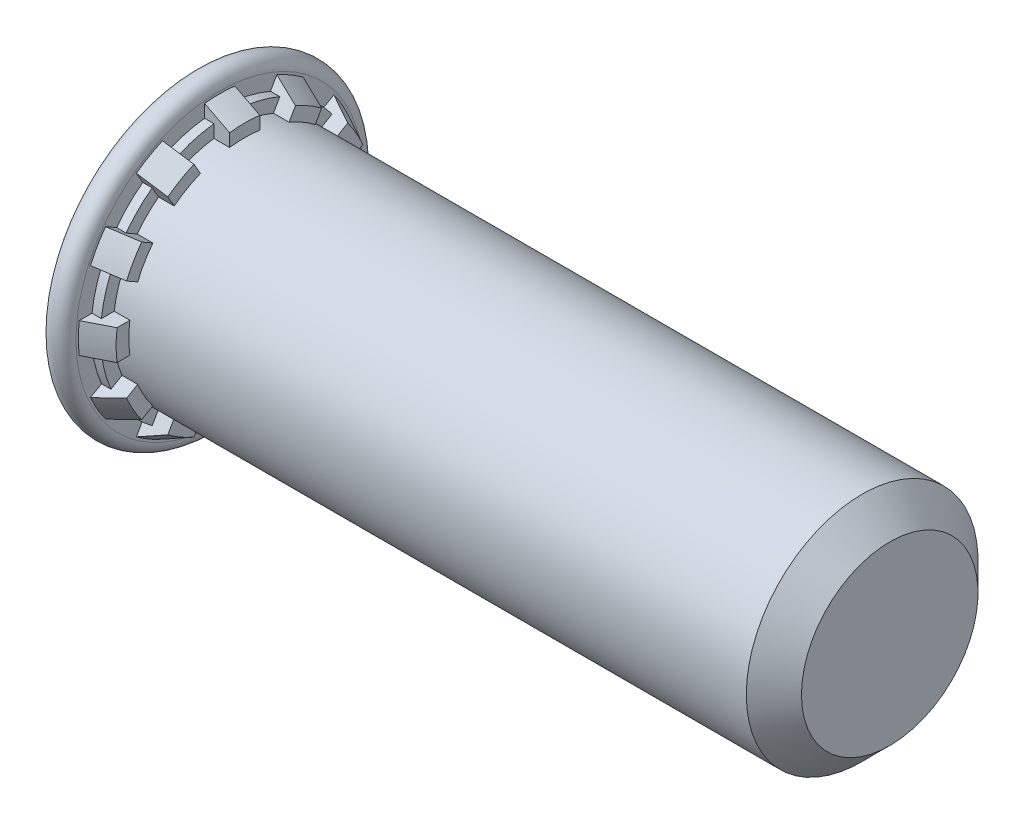
SolidWorks part; units mm, degrees
revolve "BaseBody" add sketch "BodySke" angle 360 about L6
sketch "BodySke" plane through (0, 0, 0) normal (0, 0, 1) x (1, 0, 0)
  line L0 (0, 0) -> (0, 3.9345)
  line L1 (0.6858, 3.9395) -> (0.6858, 3.8735)
  line L2 (0.6858, 3.8735) -> (1.3716, 3.5242)
  line L3 (1.3716, 3.175) -> (18.2943, 3.175)
  line L4 (19.05, 2.4193) -> (19.05, 0)
  line L5 (19.05, 0) -> (0, 0)
  line L6 (0, 0) -> (50.554, 0) construction
  line L7 (1.3716, 3.5242) -> (1.3716, 3.175)
  line L8 (19.05, 2.4193) -> (18.2943, 3.175)
  line L9 (-9.525, 4.2799) -> (9.525, 4.2799) construction
  line L11 (2.6416, 19.05) -> (2.6416, -3.175) construction
  line L13 (9.525, -4.2799) -> (-9.525, -4.2799) construction
  line L14 (0.0051, 3.9395) -> (0.0051, 3.9345)
  line L15 (0, 3.9345) -> (0.0051, 3.9345)
  arc A0 (0.0051, 3.9395) -> (0.6858, 3.9395) centre (0.3454, 3.9395) cw
  dimension "Body_ch_ang" = 45
  dimension "Length" = 19.05
  dimension "H_dia" = 8.5598
  dimension "Shoulder_lower_dia" = 7.747
  dimension "Shoulder_upper_dia" = 7.0485
  dimension "D1" = 0.0051
  dimension "D2" = 0.0051
  dimension "Shoulder_ht" = 1.3716
  dimension "Advance" = 1.27
  dimension "Minor_dia" = 4.8387
  dimension "Diameter" = 6.35
  dimension "T_dim" = 0.6858
cosmetic thread "ThreadCosmetic" [suppressed] parameters "Thread_length"=15.621, "Thread_minor"=4.8387
extrude "RibCut1" cut sketch "RibCut1Ske" against normal blind 0.4286
sketch "RibCut1Ske" plane through (1.3716, 0, 0) normal (1, 0, 0) x (0, 0, -1)
  line L0 (0.4144, 3.1478) -> (0.4144, 4.2598)
  line L1 (1.215, 2.9333) -> (1.771, 3.8963)
  line L2 (0, 0) -> (0, 4.9784) construction
  line L3 (0, 0) -> (0.4144, 3.1478) construction
  line L4 (0, 0) -> (1.215, 2.9333) construction
  arc A1 (1.215, 2.9333) -> (0.4144, 3.1478) centre (0, 0) ccw
  arc A2 (1.771, 3.8963) -> (0.4144, 4.2598) centre (0, 0) ccw
  dimension "Angle" = 30
  dimension "Inner_dia" = 6.35
  dimension "Outer_dia" = 8.5598
  dimension "Rib_root_half_angle" = 7.5
  dimension "Rib_root_gap_angle" = 15
ref_plane "Plane1" through (0, 0, 0) normal (0, 0, 1) x (1, 0, 0)
ref_plane "Plane2" through (0, 0, 0) normal (0, 1, 0) x (1, 0, 0)
ref_plane "Plane3" through (0, 0, 0) normal (1, 0, 0) x (0, 0, -1)
sketch "ThdSchSke" plane through (0, 0, 0) normal (0, 0, 1) x (1, 0, 0)
  line L0 (3.429, -2.4193) -> (2.8999, -3.175)
  line L1 (3.429, -2.4193) -> (3.9581, -3.175)
  line L2 (3.9581, -3.175) -> (3.9581, -3.9688)
  line L3 (-3.175, 0) -> (5.1513, 0) construction
  line L5 (3.9581, -3.9688) -> (2.8999, -3.9688)
  line L6 (2.8999, -3.9688) -> (2.8999, -3.175)
  line L7 (0, 3.9345) -> (0, -3.9345) construction
  dimension "Diameter" = 6.35
  dimension "SideAngle" = 55
  dimension "VeeAngle" = 70
  dimension "Thread_minor" = 4.8387
  dimension "Overcut" = 7.9375
  dimension "Start" = 3.429
revolve "ThreadSchematic" [suppressed] cut sketch "ThdSchSke" angle 360 about L3
pattern_linear "ThdSchPat" [suppressed]
sketch "RibCut2Ske" plane through (1.3716, 0, 0) normal (1, 0, 0) x (0, 0, -1)
  line L0 (0.4144, 3.4998) -> (0.4144, 4.2598)
  line L1 (1.391, 3.2381) -> (1.771, 3.8963)
  line L2 (0.4144, 3.1478) -> (0.4144, 4.9596) construction
  line L3 (0, 0) -> (0, 5.0239) construction
  line L4 (0, 0) -> (0.4144, 3.1478) construction
  line L5 (0, 0) -> (1.215, 2.9333) construction
  line L6 (1.215, 2.9333) -> (2.1244, 4.5085) construction
  arc A1 (1.391, 3.2381) -> (0.4144, 3.4998) centre (0, 0) ccw
  arc A2 (1.771, 3.8963) -> (0.4144, 4.2598) centre (0, 0) ccw
  circle A4 centre (0, 0) radius 3.175 construction
  dimension "Angle" = 30
  dimension "Outer_dia" = 8.5598
  dimension "Rib_root_half_angle" = 7.5
  dimension "Rib_root_gap_angle" = 15
extrude "RibCut2" cut sketch "RibCut2Ske" against normal blind 0.6858
pattern_circular "RibCutsPat" count 12 every 30 about axis through (0, 0, 0) along (1, 0, 0) of "RibCut2", "RibCut1"
equation "' \"Length@BodySke\" = 0.75"
equation "' \"H_dia@BodySke\" = 0.337"
equation "' \"Start@ThdSchSke\" = 0.135"
equation "' \"Diameter@BodySke\" = 0.25"
equation "' \"Minor_dia@BodySke\" =0.1905"
equation "' \"Minor_dia@BodySke\" = 0.1905"
equation "' \"Advance@BodySke\" = 0.05"
equation "\"T_dim@BodySke\" = \"Start@ThdSchSke\" * 0.2"
equation "\"Shoulder_ht@BodySke\" = \"Start@ThdSchSke\" * 0.4"
equation "\"Shoulder_lower_dia@BodySke\" = \"H_dia@BodySke\" - \"Start@ThdSchSke\" * 0.2 - .005"
equation "\"Shoulder_upper_dia@BodySke\" = ( \"Shoulder_lower_dia@BodySke\" + \"Diameter@BodySke\" ) /2"
equation "\"Num_ribs@RibCutsPat\" = 12"
equation "\"Angle@RibCutsPat\" = 360 / \"Num_ribs@RibCutsPat\""
equation "\"Angle@RibCut1Ske\" =\"Angle@RibCutsPat\""
equation "\"Rib_root_half_angle@RibCut1Ske\" = \"Angle@RibCut1Ske\" / 4"
equation "\"Rib_root_gap_angle@RibCut1Ske\" = \"Angle@RibCut1Ske\" - (2 * \"Rib_root_half_angle@RibCut1Ske\" )"
equation "\"Inner_dia@RibCut1Ske\" = \"Diameter@BodySke\""
equation "\"Outer_dia@RibCut1Ske\" = \"H_dia@BodySke\""
equation "\"Depth@RibCut1\" =  \"Start@ThdSchSke\" * 0.125"
equation "\"Angle@RibCut2Ske\" =\"Angle@RibCutsPat\""
equation "\"Rib_root_half_angle@RibCut2Ske\" = \"Angle@RibCut1Ske\" / 4"
equation "\"Rib_root_gap_angle@RibCut2Ske\" = \"Angle@RibCut1Ske\" - (2 * \"Rib_root_half_angle@RibCut1Ske\" )"
equation "\"Rib_root_dia@RibCut2Ske\" = \"Diameter@BodySke\""
equation "\"Inner_dia@RibCut2Ske\" = \"Shoulder_upper_dia@BodySke\""
equation "\"Outer_dia@RibCut2Ske\" = \"H_dia@BodySke\""
equation "\"Depth@RibCut2\" =  \"Start@ThdSchSke\" * 0.2"
equation "\"Thread_length@ThreadCosmetic\" = \"Length@BodySke\" - \"Start@ThdSchSke\""
equation "\"Thread_minor@ThreadCosmetic\" = \"Minor_dia@BodySke\""
equation "\"Thread_minor@ThdSchSke\" = \"Minor_dia@BodySke\""
equation "\"Diameter@ThdSchSke\" = \"Diameter@BodySke\""
equation "\"Overcut@ThdSchSke\" = \"Diameter@BodySke\" * 1.25"
equation "\"Num_threads@ThdSchPat\" = int( \"Thread_length@ThreadCosmetic\" / \"Advance@BodySke\" + 0.999 )  + 1"
equation "\"Advance@ThdSchPat\" = \"Thread_length@ThreadCosmetic\" /  (\"Num_threads@ThdSchPat\" - 1) 'relax it"
equation "\"Num_threads@ThdSchPat\" = \"Num_threads@ThdSchPat\" - sgn( \"Num_threads@ThdSchPat\" - 1) '---chamfered tips only---"
